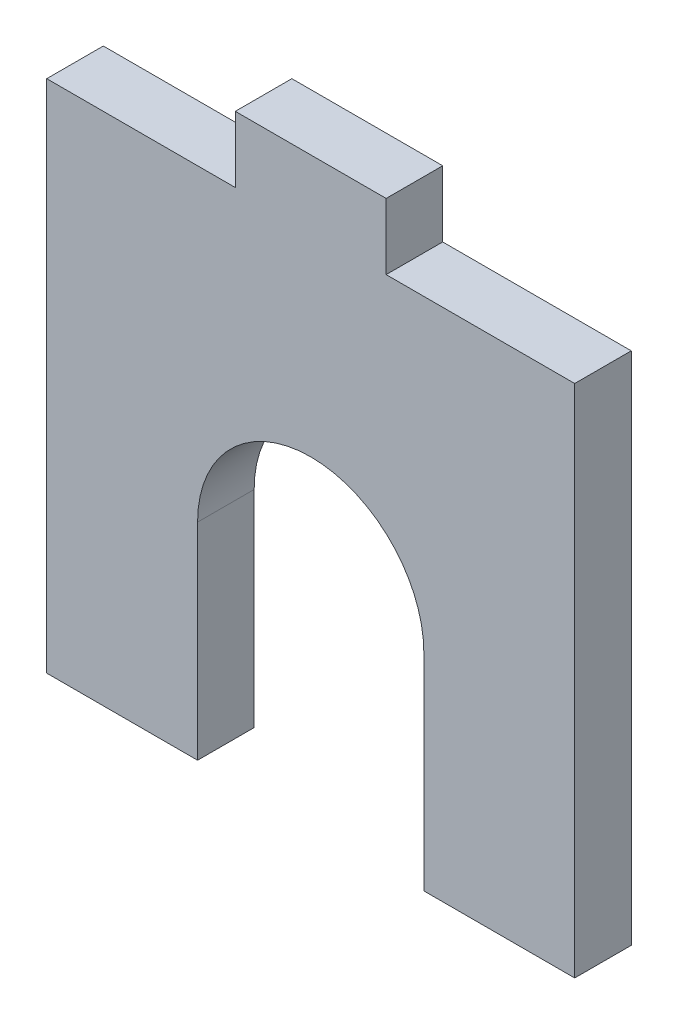
SolidWorks part; units mm, degrees
material "Chapa F.F 1020 - 1,5 mm"
ref_plane "Plano frontal" through (0, 0, 0) normal (0, 0, 1) x (1, 0, 0)
ref_plane "Plano superior" through (0, 0, 0) normal (0, 1, 0) x (1, 0, 0)
ref_plane "Plano direito" through (0, 0, 0) normal (1, 0, 0) x (0, 0, -1)
sketch "Esboço9" plane through (0, 0, 0) normal (0, 0, 1) x (1, 0, 0)
  line L0 (0, 0) -> (0, 10.9375) construction
  line L1 (-14, -10.9375) -> (-6, -10.9375)
  line L2 (-14, -10.9375) -> (-14, 16.3677)
  line L3 (-14, 16.3677) -> (-4, 16.3677)
  line L4 (14, -10.9375) -> (14, 16.3677)
  line L5 (6, 0) -> (6, -10.9375)
  line L6 (-6, 0) -> (-6, -10.9375)
  line L7 (6, -10.9375) -> (14, -10.9375)
  line L9 (-4, 16.3677) -> (-4, 19.8677)
  line L10 (-4, 19.8677) -> (4, 19.8677)
  line L11 (4, 16.3677) -> (4, 19.8677)
  line L12 (4, 16.3677) -> (14, 16.3677)
  arc A0 (6, 0) -> (-6, 0) centre (0, 0) ccw
  dimension "D3" = 27.3052
  dimension "D1" = 12
  dimension "D2" = 8
  dimension "D4" = 3.5
  dimension "D5" = 8
  dimension "D6" = 10.9375
extrude "Ressalto-extrusão1" add sketch "Esboço9" along normal blind 3
sketch "Curva-Linhas1" plane through (0, 0, 0) normal (0, 1, 0) x (1, 0, 0)
sketch "Caixa delimitadora1" plane through (0, 0, 0) normal (0, 1, 0) x (1, 0, 0)
